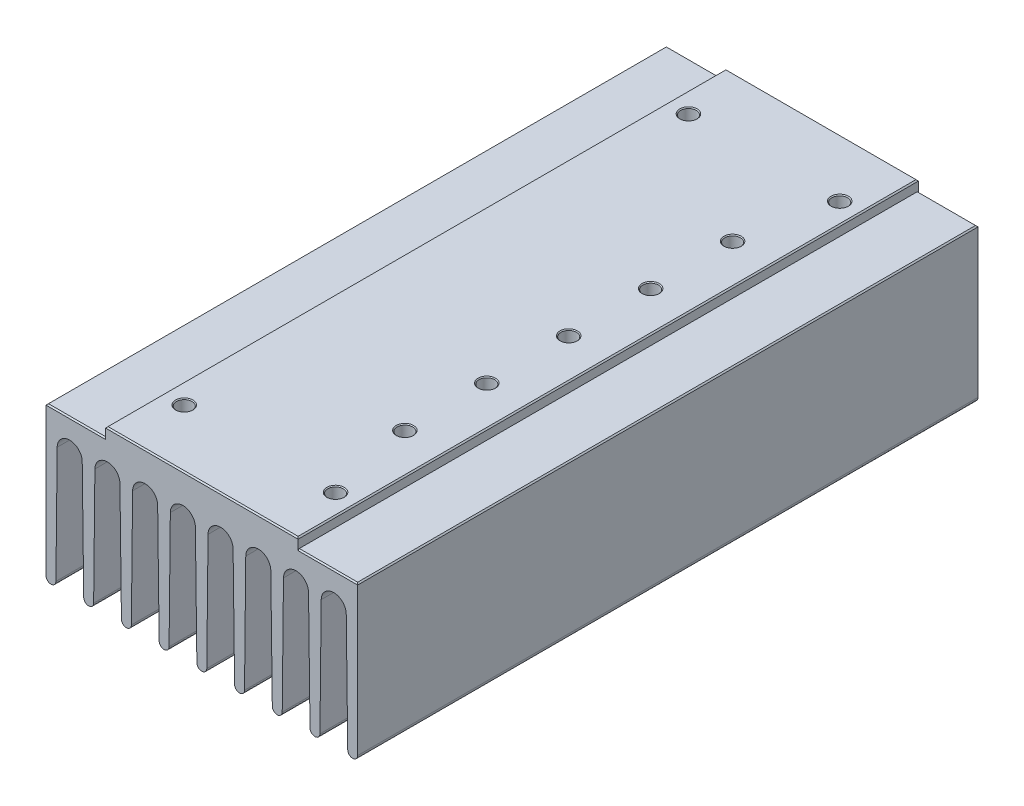
SolidWorks part; units mm, degrees
ref_plane "Спереди" through (0, 0, 0) normal (0, 0, 1) x (1, 0, 0)
ref_plane "Сверху" through (0, 0, 0) normal (0, 1, 0) x (1, 0, 0)
ref_plane "Справа" through (0, 0, 0) normal (1, 0, 0) x (0, 0, -1)
sketch "Эскиз1" plane through (0, 0, 0) normal (0, 0, 1) x (1, 0, 0)
  line L0 (-19.4, 0) -> (19.4, 0)
  line L21 (-29.4001, -32.0107) -> (-29.1482, -8.473)
  line L22 (-23.7999, -32.0128) -> (-24.1002, -8.4678)
  line L23 (-21.8001, -32.0107) -> (-21.5482, -8.473)
  line L24 (-16.1999, -32.0128) -> (-16.5002, -8.4678)
  line L25 (-14.2001, -32.0107) -> (-13.9482, -8.473)
  line L26 (-8.5999, -32.0128) -> (-8.9002, -8.4678)
  line L27 (-6.6001, -32.0107) -> (-6.3482, -8.473)
  line L28 (-0.9999, -32.0128) -> (-1.3002, -8.4678)
  line L29 (0.9999, -32.0107) -> (1.2518, -8.473)
  line L30 (6.6001, -32.0128) -> (6.2998, -8.4678)
  line L31 (8.5999, -32.0107) -> (8.8518, -8.473)
  line L32 (14.2001, -32.0128) -> (13.8998, -8.4678)
  line L33 (16.1999, -32.0107) -> (16.4518, -8.473)
  line L34 (21.8001, -32.0128) -> (21.4998, -8.4678)
  line L35 (23.7999, -32.0107) -> (24.0518, -8.473)
  line L36 (29.4001, -32.0128) -> (29.0998, -8.4678)
  line L37 (-31.4, -6.0005) -> (-31.4, -32)
  line L38 (31.4, -6.0005) -> (31.4, -32)
  line L39 (31.4, -2) -> (31.4, -6.0005)
  line L40 (-31.4, -2) -> (-31.4, -6.0005)
  line L41 (-31.4, -2) -> (-19.4, -2)
  line L42 (-19.4, -2) -> (-19.4, 0)
  line L43 (0, 5) -> (0, -35) construction
  line L44 (19.4, -2) -> (19.4, 0)
  line L45 (31.4, -2) -> (19.4, -2)
  arc A17 (-29.1482, -8.473) -> (-24.1002, -8.4678) centre (-26.6242, -8.5) cw
  arc A18 (-21.5482, -8.473) -> (-16.5002, -8.4678) centre (-19.0242, -8.5) cw
  arc A19 (-13.9482, -8.473) -> (-8.9002, -8.4678) centre (-11.4242, -8.5) cw
  arc A20 (-6.3482, -8.473) -> (-1.3002, -8.4678) centre (-3.8242, -8.5) cw
  arc A21 (1.2518, -8.473) -> (6.2998, -8.4678) centre (3.7758, -8.5) cw
  arc A22 (8.8518, -8.473) -> (13.8998, -8.4678) centre (11.3758, -8.5) cw
  arc A23 (16.4518, -8.473) -> (21.4998, -8.4678) centre (18.9758, -8.5) cw
  arc A24 (24.0518, -8.473) -> (29.0998, -8.4678) centre (26.5758, -8.5) cw
  arc A25 (-29.4001, -32.0107) -> (-31.4, -32) centre (-30.4, -32) cw
  arc A26 (-21.8001, -32.0107) -> (-23.7999, -32.0128) centre (-22.8, -32) cw
  arc A27 (-14.2001, -32.0107) -> (-16.1999, -32.0128) centre (-15.2, -32) cw
  arc A28 (-6.6001, -32.0107) -> (-8.5999, -32.0128) centre (-7.6, -32) cw
  arc A29 (0.9999, -32.0107) -> (-0.9999, -32.0128) centre (0, -32) cw
  arc A30 (8.5999, -32.0107) -> (6.6001, -32.0128) centre (7.6, -32) cw
  arc A31 (16.1999, -32.0107) -> (14.2001, -32.0128) centre (15.2, -32) cw
  arc A32 (23.7999, -32.0107) -> (21.8001, -32.0128) centre (22.8, -32) cw
  arc A33 (31.4, -32) -> (29.4001, -32.0128) centre (30.4, -32) cw
extrude "Бобышка-Вытянуть1" add sketch "Эскиз1" against normal mid plane 125
hole_wizard "Сверло под метчик  спиральное M31" positions "Эскиз2" profile "Эскиз3" hole size "M3x0.5" standard "DIN"
sketch "Эскиз2" plane through (0, 0, 0) normal (0, 1, 0) x (1, 0, 0)
  point P0 (11.43, 0)
  point P11 (11.43, -16.51)
  point P12 (11.43, -33.02)
  point P18 (11.43, 16.51)
  point P19 (11.43, 33.02)
  point P30 (15.24, 50.8)
  point P44 (-15.24, 50.8)
  point P45 (-15.24, -50.8)
  point P46 (15.24, -50.8)
  dimension "D1" = 3
  dimension "D2" = 3
  dimension "D3" = 2
  dimension "D4" = 2
sketch "Эскиз3" plane through (11.43, 0, 0) normal (1, 0, 0) x (0, 0, 1)
  line L0 (0, 0) -> (0, 10.9464)
  line L1 (0, 10.9464) -> (1.575, 10)
  line L2 (1.575, 10) -> (1.575, 0.175)
  line L3 (1.575, 0.175) -> (1.75, 0)
  line L5 (1.75, 0) -> (0, 0)
  line L6 (-1.575, 0.175) -> (-1.75, 0) construction
  line L10 (0, 10.9464) -> (-1.575, 10) construction
  line L11 (0, -6.35) -> (0, 107.95) construction
  dimension "Диаметр отверстия" = 3.15
  dimension "Глубина отверстия" = 10
  dimension "Диаметр передней зенковки" = 3.5
  dimension "Угол передней зенковки" = 90
  dimension "Угол заточки сверла" = 118
chamfer "Фаска1" distance 0.25 angle 45 10 edges at (-25.4, -2, 62.5) (-25.4, -2, -62.5) (-31.4, -2, 0) (25.4, -2, 62.5) (25.4, -2, -62.5) (31.4, -2, 0) (0, 0, 62.5) (-19.4, 0, 0) (0, 0, -62.5) (19.4, 0, 0)
